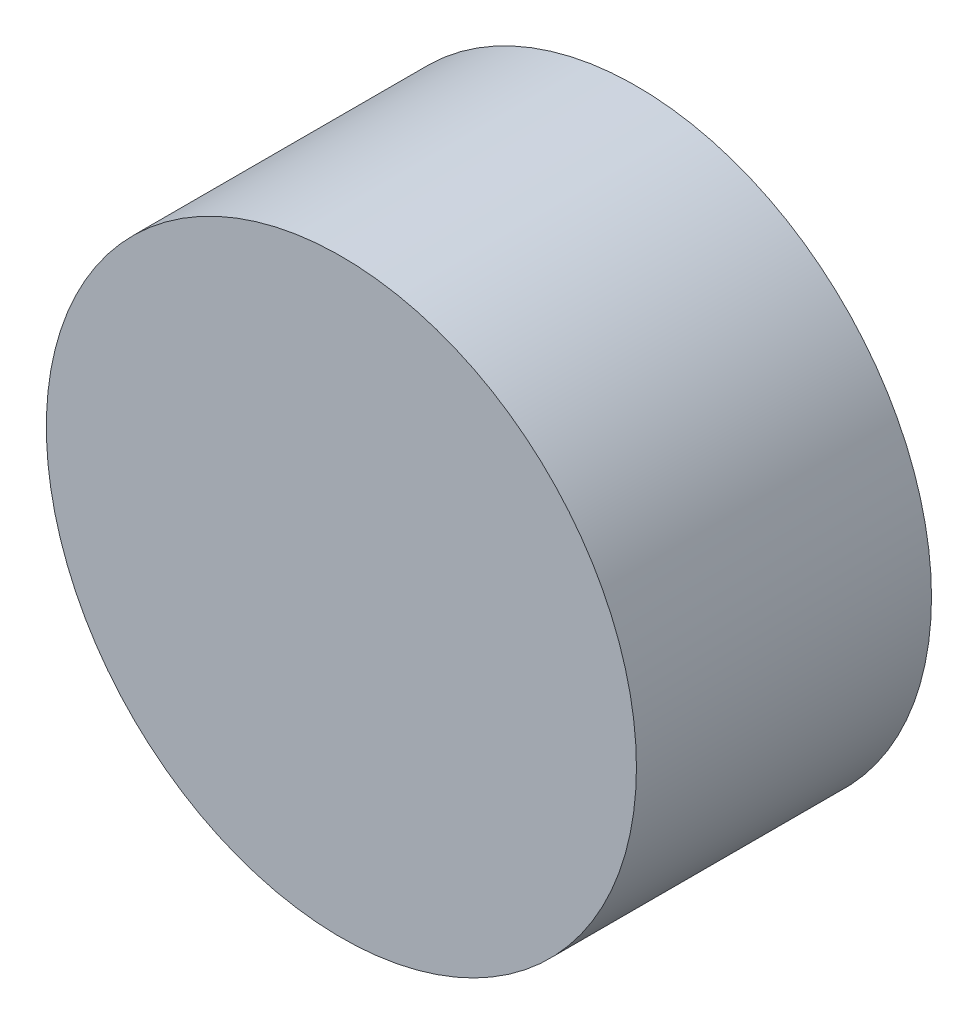
SolidWorks part; units mm, degrees
ref_plane "Front Plane" through (0, 0, 0) normal (0, 0, 1) x (1, 0, 0)
ref_plane "Top Plane" through (0, 0, 0) normal (0, 1, 0) x (1, 0, 0)
ref_plane "Right Plane" through (0, 0, 0) normal (1, 0, 0) x (0, 0, -1)
sketch "Sketch1" plane through (0, 0, 0) normal (0, 0, 1) x (1, 0, 0)
  circle A0 centre (0, 0) radius 25.4
  dimension "D1" = 50.8
extrude "Boss-Extrude1" add sketch "Sketch1" along normal blind 25.4
